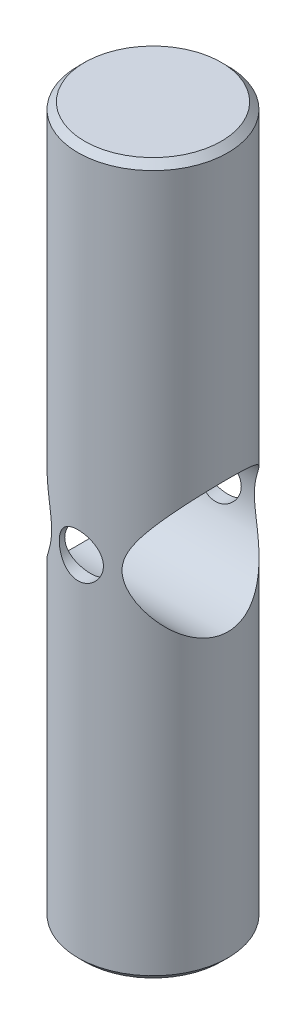
SolidWorks part; units mm, degrees
ref_plane "Front Plane" through (0, 0, 0) normal (0, 0, 1) x (1, 0, 0)
ref_plane "Top Plane" through (0, 0, 0) normal (0, 1, 0) x (1, 0, 0)
ref_plane "Right Plane" through (0, 0, 0) normal (1, 0, 0) x (0, 0, -1)
sketch "Sketch1" plane through (0, 0, 0) normal (0, 1, 0) x (1, 0, 0)
  circle A0 centre (0, 0) radius 8.495
  dimension "D1" = 16.99
extrude "Boss-Extrude1" add sketch "Sketch1" along normal blind 80.5
chamfer "Chamfer1" distance 0.75 angle 45 2 edges at (0, 0, 8.495) (0, 80.5, 8.495)
sketch "Sketch2" plane through (0, 0, 0) normal (1, 0, 0) x (0, 0, -1)
  circle A0 centre (0, 40.25) radius 7.5
  dimension "D1" = 15
extrude "Cut-Extrude1" cut sketch "Sketch2" against normal through all both and the other way through all
sketch "Sketch3" plane through (0, 0, 0) normal (0, 0, 1) x (1, 0, 0)
  line L0 (7.745, 80.5) -> (-7.745, 80.5) construction
  circle A0 centre (0, 40.25) radius 2.5
  dimension "D2" = 5
  dimension "D1" = 40.25
extrude "Cut-Extrude2" cut sketch "Sketch3" against normal through all both and the other way through all
